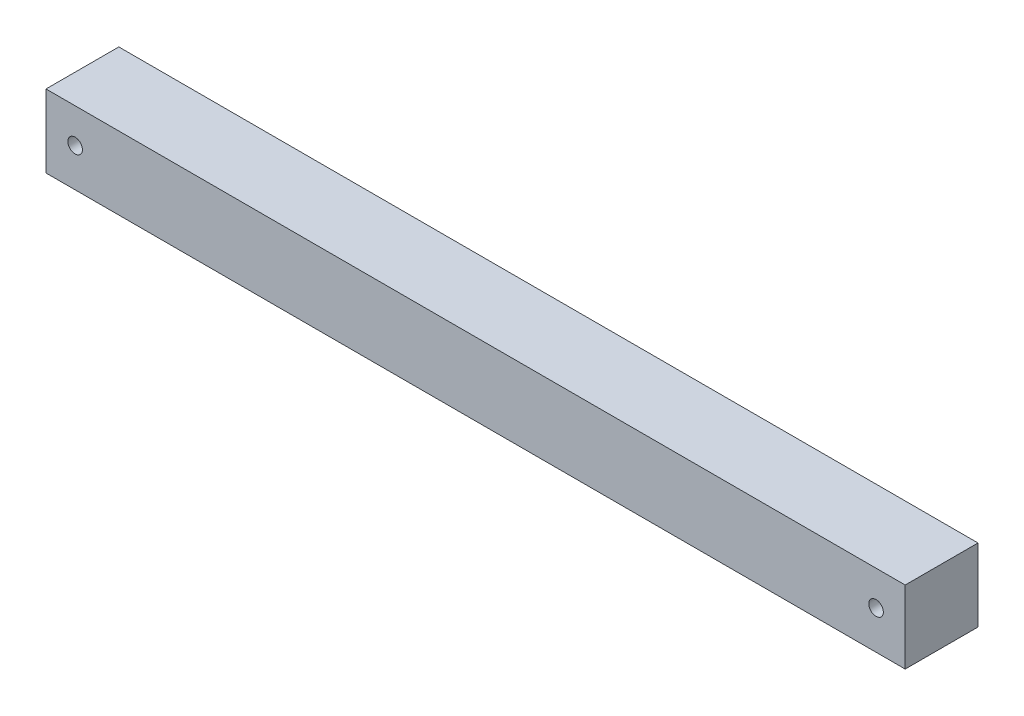
SolidWorks part; units mm, degrees
ref_plane "Plan de face" through (0, 0, 0) normal (0, 0, 1) x (1, 0, 0)
ref_plane "Plan de dessus" through (0, 0, 0) normal (0, 1, 0) x (1, 0, 0)
ref_plane "Plan de droite" through (0, 0, 0) normal (1, 0, 0) x (0, 0, -1)
sketch "Esquisse1" plane through (0, 0, 0) normal (0, 0, 1) x (1, 0, 0)
  line L1 (-19.0581, 21.2859) -> (98.9419, 21.2859)
  line L2 (-19.0581, 21.2859) -> (-19.0581, 11.2859)
  line L3 (-19.0581, 11.2859) -> (98.9419, 11.2859)
  line L4 (98.9419, 21.2859) -> (98.9419, 11.2859)
  circle A0 centre (94.9419, 16.5536) radius 1
  circle A1 centre (-15.0581, 16.5536) radius 1
  dimension "D3" = 2
  dimension "D4" = 2
  dimension "D1" = 110
  dimension "D2" = 10
  dimension "D5" = 4
  dimension "D6" = 4
extrude "Boss.-Extru.1" add sketch "Esquisse1" along normal blind 10
